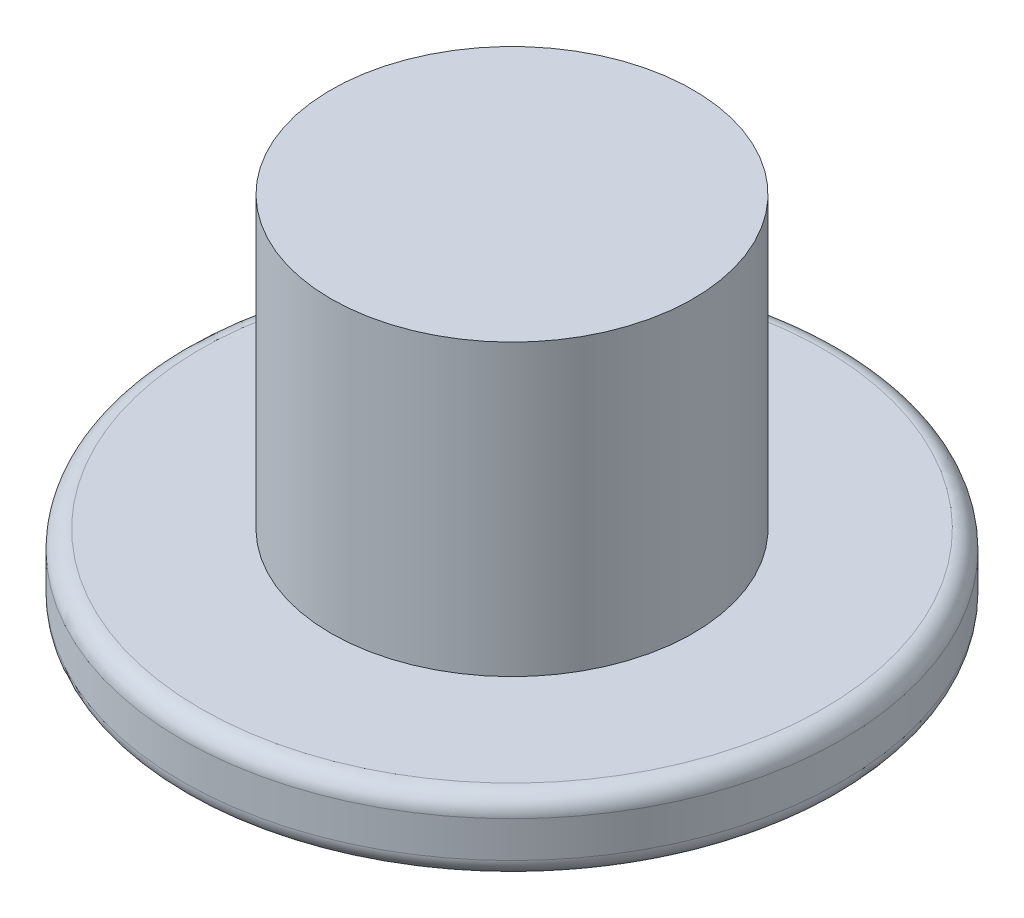
SolidWorks part; units mm, degrees
ref_plane "Front Plane" through (0, 0, 0) normal (0, 0, 1) x (1, 0, 0)
ref_plane "Top Plane" through (0, 0, 0) normal (0, 1, 0) x (1, 0, 0)
ref_plane "Right Plane" through (0, 0, 0) normal (1, 0, 0) x (0, 0, -1)
sketch "Sketch1" plane through (0, 0, 0) normal (0, 1, 0) x (1, 0, 0)
  circle A4 centre (-5.4087, -40.3067) radius 9.1
  circle A12 centre (-5.4087, -40.3067) radius 4.9321
  dimension "D5" = 18.2
extrude "Boss-Extrude5" add sketch "Sketch1" along normal blind 2 contours A4
sketch "Sketch4" plane through (0, 2, 0) normal (0, 1, 0) x (1, 0, 0)
  circle A0 centre (-5.4087, -40.3067) radius 5
  circle A1 centre (-5.4087, -40.3067) radius 9.1 construction
extrude "Boss-Extrude6" add sketch "Sketch4" along normal blind 8
sketch "Sketch5" plane through (0, 0, 0) normal (0, -1, 0) x (1, 0, 0)
  text T0 "1" font "Century Gothic" height 9
  point P1 (-5.4087, 25.1919)
  point P2 (0, 0)
  point P3 (-9.5758, 36.1339)
extrude "Cut-Extrude2" cut sketch "Sketch5" against normal blind 0.5
fillet "Fillet1" radius 0.5 2 edges at (-5.4087, 2, 49.4067) (-5.4087, 0, 49.4067)
